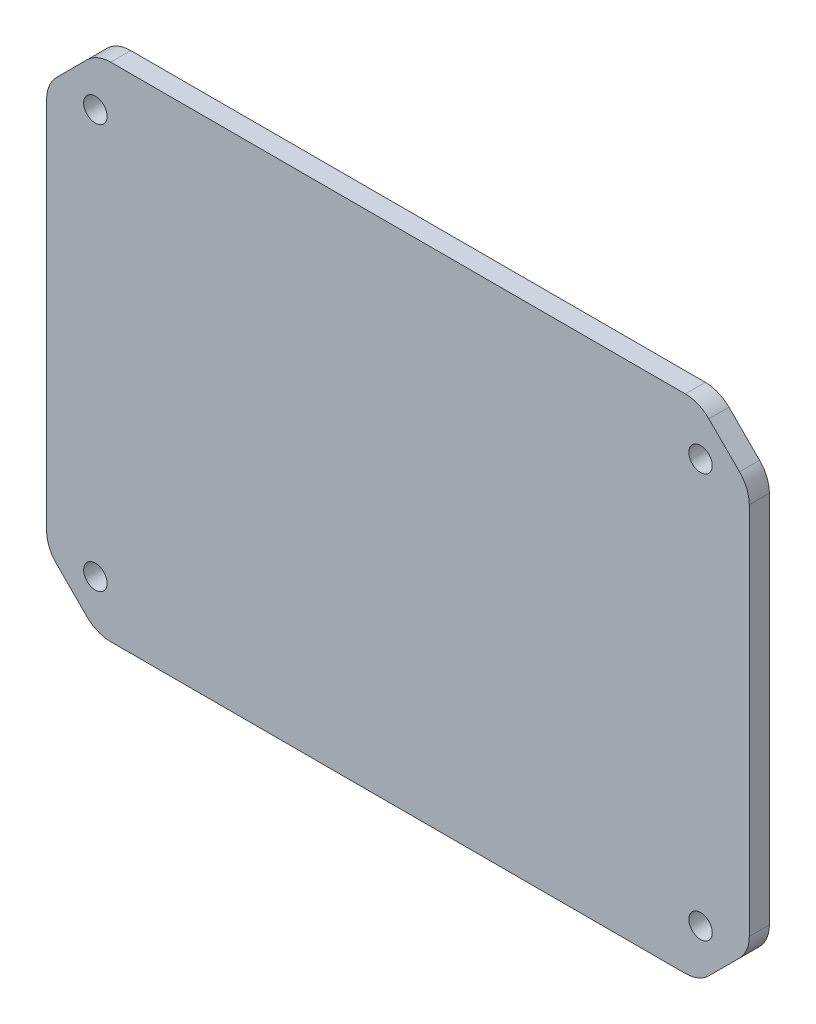
SolidWorks part; units mm, degrees
material "ПК/АБС"
ref_plane "Спереди" through (0, 0, 0) normal (0, 0, 1) x (1, 0, 0)
ref_plane "Сверху" through (0, 0, 0) normal (0, 1, 0) x (1, 0, 0)
ref_plane "Справа" through (0, 0, 0) normal (1, 0, 0) x (0, 0, -1)
sketch "Эскиз1" plane through (0, 0, 0) normal (0, 0, 1) x (1, 0, 0)
  line L0 (-51.0355, 31.4645) -> (-46.4645, 36.0355)
  line L1 (-42.9289, 37.5) -> (42.9289, 37.5)
  line L2 (-52.5, 27.9289) -> (-52.5, -27.9289)
  line L3 (-42.9289, -37.5) -> (42.9289, -37.5)
  line L4 (52.5, 27.9289) -> (52.5, -27.9289)
  line L5 (-52.5, 37.5) -> (52.5, -37.5) construction
  line L6 (-52.5, -37.5) -> (52.5, 37.5) construction
  line L7 (46.4645, 36.0355) -> (51.0355, 31.4645)
  line L8 (46.4645, -36.0355) -> (51.0355, -31.4645)
  line L9 (-51.0355, -31.4645) -> (-46.4645, -36.0355)
  line L10 (-48.75, 33.75) -> (-44.3351, 29.3351) construction
  line L11 (-52.5, 0) -> (52.5, 0) construction
  line L12 (0, 37.5) -> (0, -37.5) construction
  arc A0 (-46.4645, -36.0355) -> (-42.9289, -37.5) centre (-42.9289, -32.5) ccw
  arc A1 (-51.0355, -31.4645) -> (-52.5, -27.9289) centre (-47.5, -27.9289) cw
  arc A2 (46.4645, -36.0355) -> (42.9289, -37.5) centre (42.9289, -32.5) cw
  arc A3 (51.0355, -31.4645) -> (52.5, -27.9289) centre (47.5, -27.9289) ccw
  arc A4 (51.0355, 31.4645) -> (52.5, 27.9289) centre (47.5, 27.9289) cw
  arc A5 (46.4645, 36.0355) -> (42.9289, 37.5) centre (42.9289, 32.5) ccw
  arc A6 (-51.0355, 31.4645) -> (-52.5, 27.9289) centre (-47.5, 27.9289) ccw
  arc A7 (-46.4645, 36.0355) -> (-42.9289, 37.5) centre (-42.9289, 32.5) cw
  circle A8 centre (-45.2145, 30.2145) radius 1.75
  circle A9 centre (-45.2145, -30.2145) radius 1.75
  circle A10 centre (45.2145, -30.2145) radius 1.75
  circle A11 centre (45.2145, 30.2145) radius 1.75
  point P0 (0, 0)
  point P16 (-45, -37.5)
  point P19 (-52.5, -30)
  point P22 (45, -37.5)
  point P25 (52.5, -30)
  point P28 (52.5, 30)
  point P31 (45, 37.5)
  point P34 (-52.5, 30)
  point P37 (-45, 37.5)
  dimension "D3" = 5
  dimension "D4" = 3.5
  dimension "D1" = 75
  dimension "D2" = 105
  dimension "D9" = 5
extrude "Бобышка-Вытянуть1" add sketch "Эскиз1" along normal blind 3
